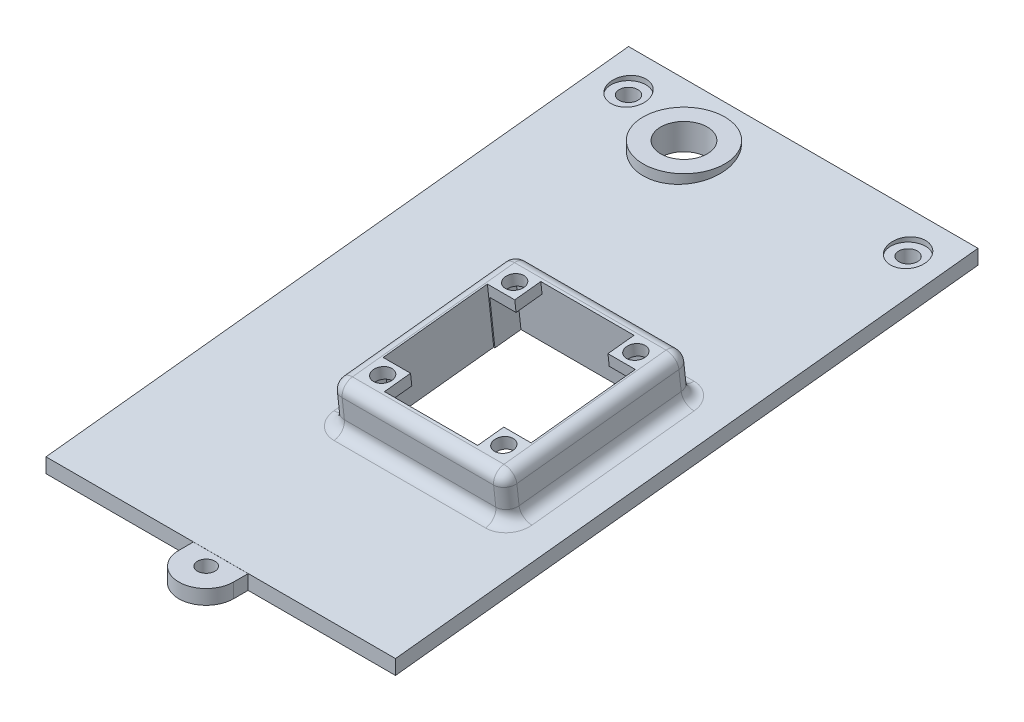
SolidWorks part; units mm, degrees
ref_plane "前视基准面" through (0, 0, 0) normal (0, 0, 1) x (1, 0, 0)
ref_plane "上视基准面" through (0, 0, 0) normal (0, 1, 0) x (1, 0, 0)
ref_plane "右视基准面" through (0, 0, 0) normal (1, 0, 0) x (0, 0, -1)
other "Configuration Table"
sketch "草图1" plane through (0, 0, 0) normal (1, 0, 0) x (0, 0, -1)
  line L0 (0, 0) -> (100, 0)
  line L1 (100, 0) -> (100, 28)
  line L2 (100, 28) -> (0, 17)
  line L3 (0, 17) -> (0, 0)
  dimension "D1" = 100
  dimension "D2" = 17
  dimension "D3" = 28
sketch "草图2" plane through (0, 0, 0) normal (1, 0, 0) x (0, 0, -1)
  line L0 (100, 28) -> (0, 17)
  line L1 (0, 17) -> (0, 14.4849)
  line L2 (0, 17) -> (0, 0) construction
  line L3 (0, 14.4849) -> (100, 25.4849)
  line L4 (100, 0) -> (100, 28) construction
  line L5 (100, 25.4849) -> (100, 28)
  dimension "D1" = 2.5
extrude "凸台-拉伸1" add sketch "草图2" against normal blind 60
ref_plane "基准面1" through (0, 25.4849, 0) normal (0, 1, 0) x (1, 0, 0)
ref_plane "基准面2" through (0, 23.4849, 0) normal (0, 1, 0) x (1, 0, 0)
sketch "草图3" plane through (0, 23.4849, 0) normal (0, 1, 0) x (1, 0, 0)
  line L0 (-60, 100) -> (0, 100) construction
  line L1 (-57.5, 97.5) -> (-50.5, 97.5)
  line L2 (-57.5, 97.5) -> (-57.5, 90.5)
  line L3 (-57.5, 90.5) -> (-50.5, 90.5)
  line L4 (-50.5, 97.5) -> (-50.5, 90.5)
  line L5 (-60, 0) -> (-60, 100) construction
  line L6 (-30, 100) -> (-30, 68.3843) construction
  line L7 (-2.5, 90.5) -> (-9.5, 90.5)
  line L8 (-9.5, 97.5) -> (-9.5, 90.5)
  line L9 (-2.5, 97.5) -> (-9.5, 97.5)
  line L10 (-2.5, 97.5) -> (-2.5, 90.5)
  dimension "D1" = 2.5
  dimension "D2" = 2.5
  dimension "D3" = 7
  dimension "D4" = 7
extrude "凸台-拉伸2" add sketch "草图3" along normal up to next
sketch "草图4" plane through (0, 23.4849, 0) normal (0, -1, 0) x (1, 0, 0)
  line L0 (-57.5, -94) -> (-50.5, -94) construction
  line L1 (-57.5, -97.5) -> (-57.5, -90.5) construction
  line L2 (-50.5, -97.5) -> (-50.5, -90.5) construction
  line L3 (-30, -100) -> (-30, -75.9911) construction
  line L4 (-60, -100) -> (0, -100) construction
  circle A0 centre (-54, -94) radius 1.6
  circle A1 centre (-6, -94) radius 1.6
  dimension "D1" = 3.2
extrude "切除-拉伸1" cut sketch "草图4" against normal through all
ref_plane "基准面3" through (0, 28, 0) normal (0, 1, 0) x (1, 0, 0)
sketch "草图5" plane through (0, 28, 0) normal (0, 1, 0) x (1, 0, 0)
  circle A0 centre (-54, 94) radius 3
  circle A1 centre (-6, 94) radius 3
  dimension "D1" = 6
  dimension "D2" = 6
extrude "切除-拉伸2" cut sketch "草图5" against normal blind 1.2
ref_plane "基准面4" through (0, 25.5, 0) normal (0, 1, 0) x (1, 0, 0)
sketch "草图6" plane through (0, 23.4849, 0) normal (0, 1, 0) x (1, 0, 0)
  line L0 (-50.5, 90.5) -> (-50.5, 97.5) construction
  line L1 (-50.5, 83.4) -> (-32.0531, 83.4)
  line L2 (-50.5, 83.4) -> (-50.5, 97.4)
  line L3 (-50.5, 97.4) -> (-32.0531, 97.4)
  line L4 (-32.0531, 83.4) -> (-32.0531, 97.4)
  line L6 (-60, 100) -> (0, 100) construction
  dimension "D1" = 2.6
  dimension "D2" = 14
  dimension "D3" = 18.4469
extrude "凸台-拉伸3" add sketch "草图6" along normal up to next
sketch "草图7" plane through (0, 23.4849, 0) normal (0, -1, 0) x (1, 0, 0)
  line L0 (-50.5, -90.5) -> (-50.5, -83.4) construction
  line L1 (-50.5, -84) -> (-32.0531, -84)
  line L2 (-50.5, -84) -> (-50.5, -81.5)
  line L3 (-50.5, -81.5) -> (-32.0531, -81.5)
  line L4 (-32.0531, -84) -> (-32.0531, -81.5)
  line L5 (-60, -100) -> (0, -100) construction
  line L6 (-32.0531, -97.4) -> (-32.0531, -83.4) construction
  dimension "D1" = 16
  dimension "D2" = 2.5
extrude "凸台-拉伸4" add sketch "草图7" along normal blind 2.5 and the other way up to next
sketch "草图8" plane through (0, 23.4849, 0) normal (0, -1, 0) x (1, 0, 0)
  line L0 (-41.2766, -97.4) -> (-41.2766, -84) construction
  line L1 (-32.0531, -97.4) -> (-50.5, -97.4) construction
  line L2 (-50.5, -84) -> (-32.0531, -84) construction
  line L3 (-60, -100) -> (0, -100) construction
  circle A0 centre (-41.2766, -90.8) radius 4
  dimension "D1" = 8
  dimension "D2" = 9.2
extrude "切除-拉伸3" cut sketch "草图8" against normal through all
sketch "草图9" plane through (0, 28, 0) normal (0, 1, 0) x (1, 0, 0)
  circle A0 centre (-41.2766, 90.8) radius 7
  dimension "D1" = 14
extrude "凸台-拉伸5" add sketch "草图9" against normal up to surface (1.782 mm away)
sketch "草图11" plane through (0, 23.4849, 0) normal (0, -1, 0) x (1, 0, 0)
  circle A0 centre (-41.2766, -90.8) radius 4
extrude "切除-拉伸5" cut sketch "草图11" against normal through all
sketch "草图12" plane through (0, 16.7968, 1.8476) normal (0, 0.994, 0.1093) x (1, 0, 0)
  line L0 (-60, 102.462) -> (0, 102.462) construction
  line L1 (-7, 60.462) -> (-37, 60.462)
  line L2 (-7, 60.462) -> (-7, 28.462)
  line L3 (-7, 28.462) -> (-37, 28.462)
  line L4 (-37, 60.462) -> (-37, 28.462)
  line L5 (0, 0) -> (0, 99.4004) construction
  dimension "D1" = 42
  dimension "D2" = 7
  dimension "D3" = 30
  dimension "D4" = 32
extrude "凸台-拉伸6" add sketch "草图12" along normal blind 7.5
sketch "草图13" plane through (0, 24.2518, 2.6677) normal (0, 0.994, 0.1093) x (1, 0, 0)
  line L10 (-9.5, 30.962) -> (-9.5, 57.962)
  line L11 (-9.5, 57.962) -> (-34.5, 57.962)
  line L12 (-34.5, 57.962) -> (-34.5, 30.962)
  line L13 (-34.5, 30.962) -> (-9.5, 30.962)
  line L14 (-9.5, 30.962) -> (-9.5, 57.962)
  line L15 (-9.5, 57.962) -> (-34.5, 57.962)
  line L16 (-34.5, 57.962) -> (-34.5, 30.962)
  line L17 (-34.5, 30.962) -> (-9.5, 30.962)
  dimension "D1" = 2.5
extrude "切除-拉伸6" cut sketch "草图13" against normal through all
sketch "草图14" plane through (0, 24.2518, 2.6677) normal (0, 0.994, 0.1093) x (1, 0, 0)
  line L0 (-22, 57.962) -> (-22, 30.962) construction
  line L1 (-34.5, 57.962) -> (-30, 57.962)
  line L2 (-34.5, 57.962) -> (-34.5, 53.462)
  line L3 (-34.5, 53.462) -> (-30, 53.462)
  line L4 (-30, 57.962) -> (-30, 53.462)
  line L5 (-34.5, 30.962) -> (-30, 30.962)
  line L6 (-34.5, 30.962) -> (-34.5, 35.462)
  line L7 (-34.5, 35.462) -> (-30, 35.462)
  line L8 (-30, 30.962) -> (-30, 35.462)
  line L9 (-9.5, 30.962) -> (-14, 30.962)
  line L10 (-9.5, 30.962) -> (-9.5, 35.462)
  line L11 (-9.5, 35.462) -> (-14, 35.462)
  line L12 (-14, 30.962) -> (-14, 35.462)
  line L13 (-9.5, 57.962) -> (-14, 57.962)
  line L14 (-9.5, 57.962) -> (-9.5, 53.462)
  line L15 (-9.5, 53.462) -> (-14, 53.462)
  line L16 (-14, 57.962) -> (-14, 53.462)
  line L17 (-9.5, 57.962) -> (-34.5, 57.962) construction
  line L18 (-34.5, 30.962) -> (-9.5, 30.962) construction
  line L19 (-34.5, 44.462) -> (-9.5, 44.462) construction
  line L20 (-34.5, 57.962) -> (-34.5, 30.962) construction
  line L21 (-9.5, 30.962) -> (-9.5, 57.962) construction
  circle A0 centre (-32.4, 55.862) radius 1.6
  circle A1 centre (-11.6, 55.862) radius 1.6
  circle A2 centre (-11.6, 33.062) radius 1.6
  circle A3 centre (-32.4, 33.062) radius 1.6
  dimension "D1" = 3.2
  dimension "D2" = 2.1
  dimension "D3" = 2.1
  dimension "D4" = 4.5
extrude "凸台-拉伸7" add sketch "草图14" against normal blind 2
fillet "圆角2" radius 2 12 edges at (-37, 21.6583, -42.3477) (-37, 29.1133, -41.5277) (-22, 23.4077, -58.2518) (-22, 30.8627, -57.4318) (-37, 27.1352, -57.8418) (-7, 21.6583, -42.3477) (-7, 29.1133, -41.5277) (-7, 27.1352, -57.8418) (-37, 23.6363, -26.0337) (-22, 19.9088, -26.4437) (-22, 27.3638, -25.6236) (-7, 23.6363, -26.0337)
sketch "草图15" plane through (0, 24.2518, 2.6677) normal (0, 0.994, 0.1093) x (1, 0, 0)
  line L1 (-34.7, 53.462) -> (-9.3, 53.462)
  line L2 (-34.7, 53.462) -> (-34.7, 35.462)
  line L3 (-34.7, 35.462) -> (-9.3, 35.462)
  line L4 (-9.3, 53.462) -> (-9.3, 35.462)
  line L6 (-14, 53.462) -> (-9.5, 53.462) construction
  line L7 (-30, 35.462) -> (-34.5, 35.462) construction
  line L8 (-34.5, 53.462) -> (-34.5, 35.462) construction
  line L9 (-9.5, 35.462) -> (-9.5, 53.462) construction
  dimension "D1" = 0.2
  dimension "D2" = 0.2
extrude "切除-拉伸7" cut sketch "草图15" against normal through all
ref_plane "基准面5" through (0, 14.4849, 0) normal (0, 1, 0) x (1, 0, 0)
sketch "草图16" plane through (0, 14.4849, 0) normal (0, 1, 0) x (1, 0, 0)
  line L0 (-30, 0) -> (-30, -15.6023) construction
  line L1 (-60, 0) -> (0, 0) construction
  line L2 (-34.7, -2.5) -> (-34.7, 0)
  line L3 (-34.7, 0) -> (-25.3, 0)
  line L4 (-25.3, 0) -> (-25.3, -2.5)
  circle A0 centre (-30, -2.5) radius 1.5
  arc A1 (-34.7, -2.5) -> (-25.3, -2.5) centre (-30, -2.5) ccw
  dimension "D1" = 3
  dimension "D3" = 9.4
  dimension "D2" = 2.5
extrude "凸台-拉伸8" add sketch "草图16" along normal blind 2.5
